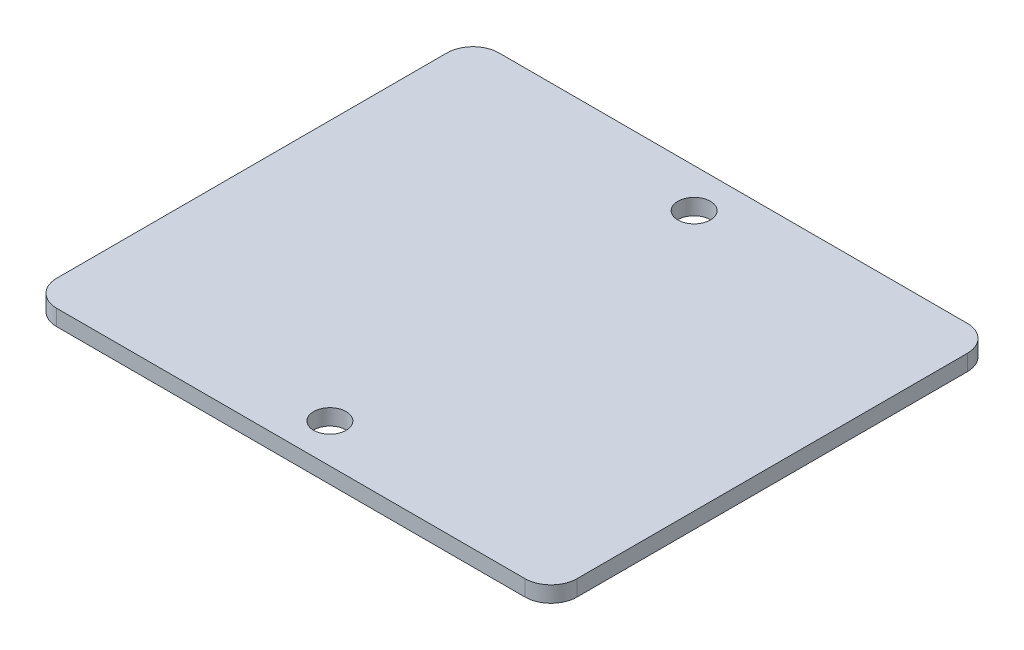
SolidWorks part; units mm, degrees
ref_plane "Front Plane" through (0, 0, 0) normal (0, 0, 1) x (1, 0, 0)
ref_plane "Top Plane" through (0, 0, 0) normal (0, 1, 0) x (1, 0, 0)
ref_plane "Right Plane" through (0, 0, 0) normal (1, 0, 0) x (0, 0, -1)
sketch "Sketch1" plane through (0, 0, 0) normal (0, 1, 0) x (1, 0, 0)
  line L0 (0, 0) -> (19.8073, 0) construction
  line L1 (-25.4, -21.59) -> (25.4, -21.59)
  line L2 (-25.4, -21.59) -> (-25.4, 21.59)
  line L3 (-25.4, 21.59) -> (25.4, 21.59)
  line L4 (25.4, -21.59) -> (25.4, 21.59)
  line L5 (-25.4, -21.59) -> (25.4, 21.59) construction
  line L6 (-25.4, 21.59) -> (25.4, -21.59) construction
  circle A0 centre (0, 17.78) radius 1.5875
  circle A1 centre (0, -17.78) radius 1.5875
  point P0 (0, 0)
  dimension "D3" = 3.175
  dimension "D1" = 50.8
  dimension "D2" = 43.18
  dimension "D4" = 35.56
extrude "Boss-Extrude1" add sketch "Sketch1" along normal blind 1.56
fillet "Fillet1" radius 2.54 4 edges at (-25.4, 0.78, -21.59) (-25.4, 0.78, 21.59) (25.4, 0.78, 21.59) (25.4, 0.78, -21.59)
